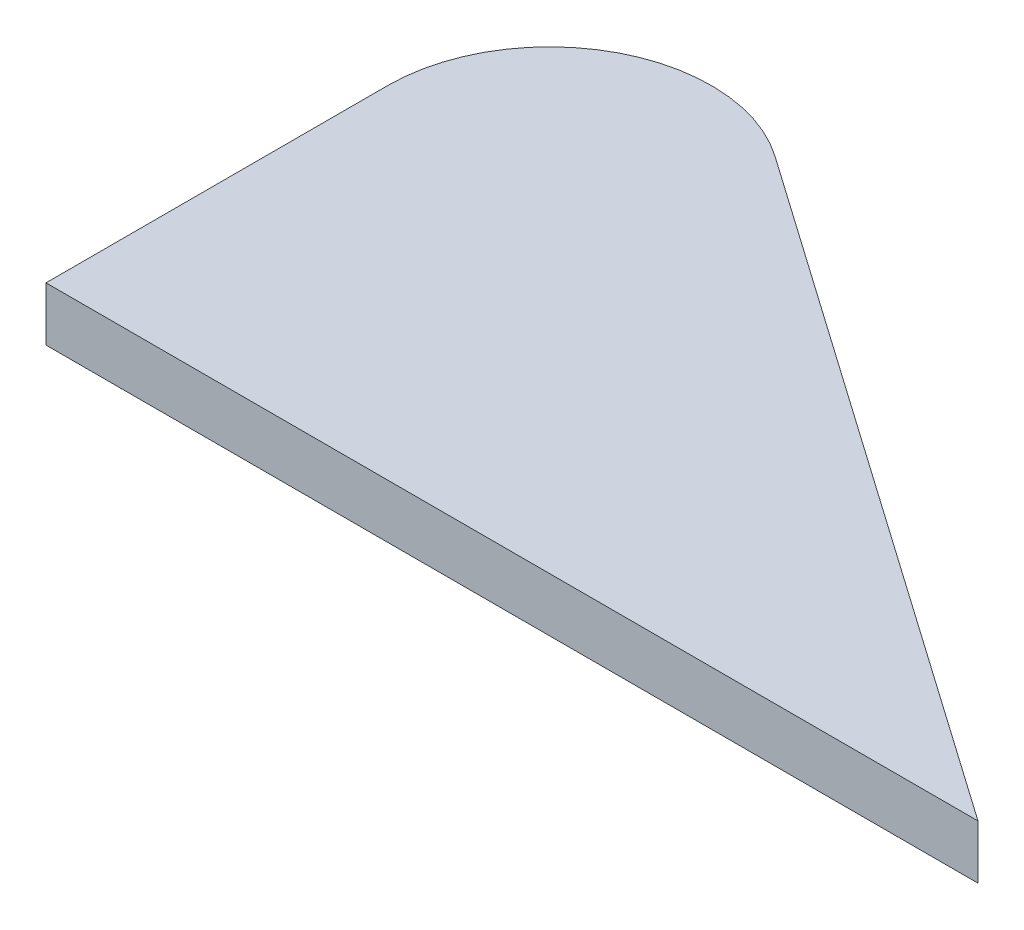
SolidWorks part; units mm, degrees
ref_plane "Front Plane" through (0, 0, 0) normal (0, 0, 1) x (1, 0, 0)
ref_plane "Top Plane" through (0, 0, 0) normal (0, 1, 0) x (1, 0, 0)
ref_plane "Right Plane" through (0, 0, 0) normal (1, 0, 0) x (0, 0, -1)
sketch "Sketch1" plane through (0, 0, 0) normal (0, 1, 0) x (1, 0, 0)
  line L0 (19.05, 63.5) -> (19.05, 0) construction
  line L5 (19.05, 0) -> (109.7374, 0)
  line L6 (109.7374, 0) -> (29.9766, 55.8491)
  line L7 (0, 0) -> (19.05, 0)
  line L9 (0, 0) -> (0, 40.2442)
  arc A1 (29.9766, 55.8491) -> (0, 40.2442) centre (19.05, 40.2442) ccw
  circle A2 centre (19.05, 40.2442) radius 4.7625
  dimension "D3" = 38.1
  dimension "D5" = 9.525
  dimension "D1" = 35
  dimension "D2" = 63.5
  dimension "D4" = 55.8491
extrude "Boss-Extrude2" add sketch "Sketch1" along normal blind 6.35 contours L6 A1 L9 L7 L5
